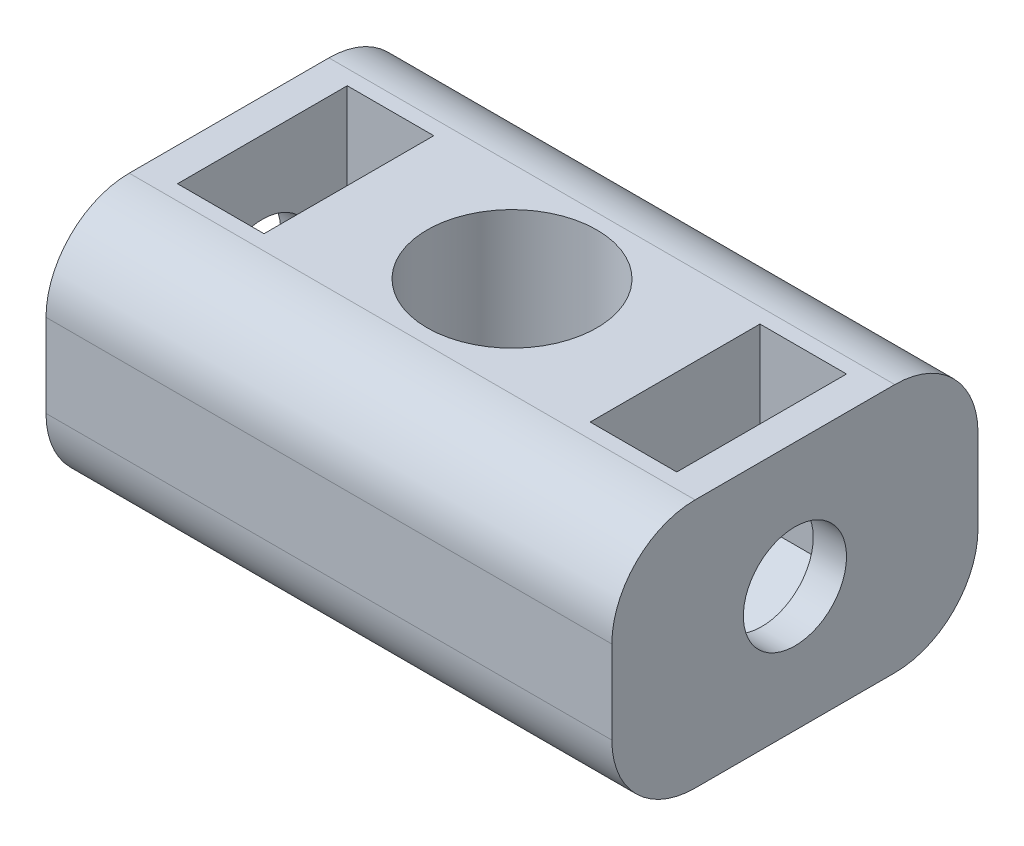
SolidWorks part; units mm, degrees
ref_plane "Alzado" through (0, 0, 0) normal (0, 0, 1) x (1, 0, 0)
ref_plane "Planta" through (0, 0, 0) normal (0, 1, 0) x (1, 0, 0)
ref_plane "Vista lateral" through (0, 0, 0) normal (1, 0, 0) x (0, 0, -1)
sketch "Croquis1" plane through (0, 0, 0) normal (0, 1, 0) x (1, 0, 0)
  line L0 (17, 22) -> (17, 0) construction
  line L1 (0, 0) -> (34, 0)
  line L2 (0, 0) -> (0, 22)
  line L3 (0, 22) -> (34, 22)
  line L4 (34, 0) -> (34, 22)
  circle A0 centre (17, 11) radius 5.1
  dimension "D3" = 10.2
  dimension "D1" = 34
  dimension "D2" = 22
extrude "Saliente-Extruir1" add sketch "Croquis1" along normal blind 15
ref_plane "Plano1" through (2, 0, 0) normal (-1, 0, 0) x (0, 0, 1)
sketch "Croquis2" plane through (2, 0, 0) normal (-1, 0, 0) x (0, 0, 1)
  line L0 (-11, 15) -> (-11, 0) construction
  line L1 (-22, 15) -> (0, 15) construction
  line L2 (-22, 0) -> (0, 0) construction
  line L3 (-16.1, 10.4445) -> (-16.1, 15)
  line L4 (-11, 1.611) -> (-5.9, 4.5555)
  line L5 (-5.9, 4.5555) -> (-5.9, 10.4445)
  line L6 (-5.9, 10.4445) -> (-11, 13.389) construction
  line L7 (-11, 13.389) -> (-16.1, 10.4445) construction
  line L8 (-16.1, 10.4445) -> (-16.1, 4.5555)
  line L9 (-16.1, 4.5555) -> (-11, 1.611)
  line L10 (-16.1, 15) -> (-5.9, 15)
  line L11 (-5.9, 15) -> (-5.9, 10.4445)
  circle A0 centre (-11, 7.5) radius 5.1 construction
  point P7 (-16.1, 7.5)
  point P15 (0, 0)
  point P20 (-19.6485, 15)
  dimension "D1" = 10.2
extrude "Cortar-Extruir1" cut sketch "Croquis2" against normal blind 5.2
ref_plane "Plano2" through (32, 0, 0) normal (1, 0, 0) x (0, 0, -1)
sketch "Croquis3" plane through (32, 0, 0) normal (1, 0, 0) x (0, 0, -1)
  line L0 (5.9, 15) -> (5.9, 0) construction
  line L1 (16.1, 0) -> (16.1, 15) construction
  line L2 (0, 15) -> (22, 15) construction
  line L3 (16.1, 4.5555) -> (11, 1.611) construction
  line L4 (11, 1.611) -> (5.9, 4.5555) construction
  line L5 (5.9, 15) -> (5.9, 4.5555)
  line L6 (16.1, 4.5555) -> (16.1, 15)
  line L7 (5.9, 15) -> (16.1, 15)
  line L8 (16.1, 4.5555) -> (11, 1.611)
  line L9 (11, 1.611) -> (5.9, 4.5555)
extrude "Cortar-Extruir2" cut sketch "Croquis3" against normal blind 5.2
ref_plane "Plano3" through (0, 7.5, 0) normal (0, 1, 0) x (1, 0, 0)
sketch "Croquis5" plane through (34, 0, 0) normal (1, 0, 0) x (0, 0, -1)
  line L0 (11, 1.611) -> (11, 15) construction
  line L1 (0, 15) -> (22, 15) construction
  line L2 (0, 7.5) -> (22, 7.5) construction
  line L3 (0, 15) -> (0, 0) construction
  line L4 (22, 15) -> (22, 0) construction
  circle A0 centre (11, 7.5) radius 3.1
  dimension "D1" = 6.2
extrude "Cortar-Extruir4" cut sketch "Croquis5" against normal blind 4
sketch "Croquis6" plane through (0, 0, 0) normal (-1, 0, 0) x (0, 0, 1)
  circle A0 centre (-11, 7.5) radius 3.1 construction
  circle A1 centre (-11, 7.5) radius 3.1
extrude "Cortar-Extruir5" cut sketch "Croquis6" against normal blind 4
fillet "Redondeo1" radius 5 4 edges at (17, 0, 0) (17, 0, -22) (17, 15, 0) (17, 15, -22)
